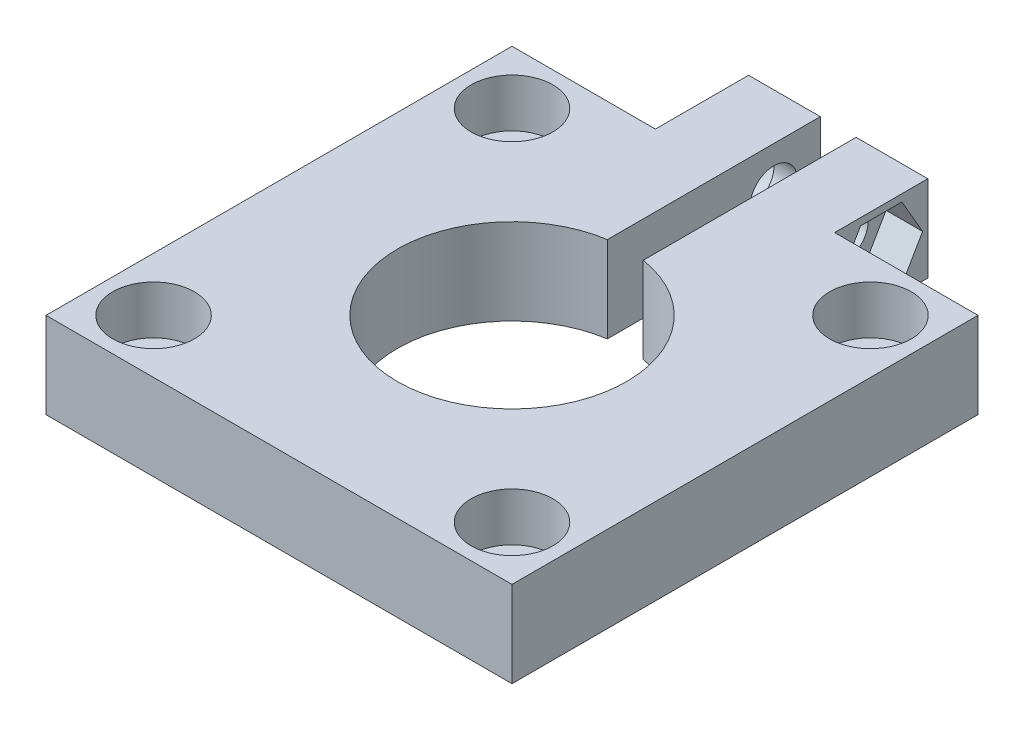
SolidWorks part; units mm, degrees
ref_plane "Front Plane" through (0, 0, 0) normal (0, 0, 1) x (1, 0, 0)
ref_plane "Top Plane" through (0, 0, 0) normal (0, 1, 0) x (1, 0, 0)
ref_plane "Right Plane" through (0, 0, 0) normal (1, 0, 0) x (0, 0, -1)
sketch "Sketch1" plane through (0, 0, 0) normal (0, 1, 0) x (1, 0, 0)
  line L1 (-32.5, 32.5) -> (32.5, 32.5)
  line L2 (-32.5, 32.5) -> (-32.5, -32.5)
  line L3 (-32.5, -32.5) -> (32.5, -32.5)
  line L4 (32.5, 32.5) -> (32.5, -32.5)
  line L5 (-32.5, 32.5) -> (32.5, -32.5) construction
  line L6 (-32.5, -32.5) -> (32.5, 32.5) construction
  point P0 (0, 0)
  dimension "D1" = 65
  dimension "D2" = 65
extrude "Boss-Extrude1" add sketch "Sketch1" along normal blind 12
sketch "Sketch3" plane through (0, 12, 0) normal (0, 1, 0) x (-1, 0, 0)
  circle A0 centre (0, 0) radius 16
  dimension "D1" = 32
extrude "Cut-Extrude1" cut sketch "Sketch3" against normal blind 12
sketch "Sketch4" plane through (0, 12, 0) normal (0, 1, 0) x (-1, 0, 0)
  line L0 (-32.5, -32.5) -> (32.5, -32.5) construction
  line L1 (2.5, -52.5) -> (-2.5, -52.5)
  line L2 (2.5, -52.5) -> (2.5, -12.5)
  line L3 (2.5, -12.5) -> (-2.5, -12.5)
  line L4 (-2.5, -52.5) -> (-2.5, -12.5)
  line L5 (2.5, -52.5) -> (-2.5, -12.5) construction
  line L6 (2.5, -12.5) -> (-2.5, -52.5) construction
  point P0 (0, -32.5)
  dimension "D1" = 40
extrude "Cut-Extrude2" cut sketch "Sketch4" against normal blind 12
sketch "Sketch5" plane through (0, 12, 0) normal (0, 1, 0) x (-1, 0, 0)
  line L1 (2.5, -32.5) -> (12.5, -32.5)
  line L2 (2.5, -32.5) -> (2.5, -45.5)
  line L3 (2.5, -45.5) -> (12.5, -45.5)
  line L4 (12.5, -32.5) -> (12.5, -45.5)
  dimension "D1" = 13
  dimension "D2" = 10
extrude "Boss-Extrude4" add sketch "Sketch5" against normal blind 12
pattern_linear "LPattern1" count 2 spacing 15 along (1, 0, 0) of "Boss-Extrude4"
hole_wizard "CBORE for M6 Hex Socket Head Cap Screw1" positions "Sketch7" profile "Sketch6" counterbore size "M6" standard "DIN" end condition through all
sketch "Sketch7" plane through (-12.5, 0, 0) normal (-1, 0, 0) x (0, 0, 1)
  line L0 (-45.5, 0) -> (-32.5, 0) construction
  line L1 (-45.5, 0) -> (-45.5, 12) construction
  point P0 (-39, 6)
  point P10 (-39, 0)
  point P11 (-45.5, 6)
  dimension "D1" = 0
  dimension "D2" = 0
sketch "Sketch6" plane through (-12.5, 6, -39) normal (0, 1, 0) x (0, 0, 1)
  line L0 (0, 0) -> (0, 45)
  line L1 (0, 45) -> (3.3, 45)
  line L3 (3.3, 45) -> (3.3, 6.75)
  line L4 (3.3, 6.75) -> (5.25, 6.75)
  line L5 (5.25, 6.75) -> (5.25, 0)
  line L7 (5.25, 0) -> (0, 0)
  line L11 (0, -6.35) -> (0, 107.95) construction
  dimension "Thru Hole Dia." = 6.6
  dimension "Thru Hole Depth" = 45
  dimension "C'Bore Dia." = 10.5
  dimension "C'Bore Depth" = 6.75
sketch "Sketch9" plane through (12.5, 0, 0) normal (1, 0, 0) x (0, 0, -1)
  line L0 (32.5, 0) -> (45.5, 0) construction
  line L1 (44.7735, 6) -> (41.8868, 11)
  line L2 (41.8868, 11) -> (36.1132, 11)
  line L3 (36.1132, 11) -> (33.2265, 6)
  line L4 (33.2265, 6) -> (36.1132, 1)
  line L5 (36.1132, 1) -> (41.8868, 1)
  line L6 (41.8868, 1) -> (44.7735, 6)
  line L8 (45.5, 0) -> (45.5, 12) construction
  circle A0 centre (39, 6) radius 5 construction
  point P1 (39, 0)
  point P11 (45.5, 6)
  dimension "D1" = 5
  dimension "D2" = 0
  dimension "D3" = 0
extrude "Cut-Extrude3" cut sketch "Sketch9" against normal blind 5.1
hole_wizard "CBORE for M6 Hex Socket Head Cap Screw2" positions "Sketch11" profile "Sketch10" counterbore size "M6" standard "DIN" end condition through all
sketch "Sketch11" plane through (0, 12, 0) normal (0, 1, 0) x (-1, 0, 0)
  point P0 (25, -25)
  dimension "D1" = 25
  dimension "D2" = 25
sketch "Sketch10" plane through (-25, 12, -25) normal (1, 0, 0) x (0, 0, 1)
  line L0 (0, 0) -> (0, 12)
  line L1 (0, 12) -> (3.75, 12)
  line L3 (3.75, 12) -> (3.75, 6.75)
  line L4 (3.75, 6.75) -> (5.7, 6.75)
  line L5 (5.7, 6.75) -> (5.7, 0)
  line L7 (5.7, 0) -> (0, 0)
  line L11 (0, -6.35) -> (0, 107.95) construction
  dimension "Thru Hole Dia." = 7.5
  dimension "Thru Hole Depth" = 12
  dimension "C'Bore Dia." = 11.4
  dimension "C'Bore Depth" = 6.75
hole_wizard "CBORE for M6 Hex Socket Head Cap Screw3" positions "Sketch13" profile "Sketch12" counterbore size "M6" standard "DIN" end condition through all
sketch "Sketch13" plane through (0, 12, 0) normal (0, 1, 0) x (-1, 0, 0)
  point P0 (-25, -25)
  dimension "D1" = 25
  dimension "D2" = 25
sketch "Sketch12" plane through (25, 12, -25) normal (1, 0, 0) x (0, 0, 1)
  line L0 (0, 0) -> (0, 12)
  line L1 (0, 12) -> (3.75, 12)
  line L3 (3.75, 12) -> (3.75, 6.75)
  line L4 (3.75, 6.75) -> (5.7, 6.75)
  line L5 (5.7, 6.75) -> (5.7, 0)
  line L7 (5.7, 0) -> (0, 0)
  line L11 (0, -6.35) -> (0, 107.95) construction
  dimension "Thru Hole Dia." = 7.5
  dimension "Thru Hole Depth" = 12
  dimension "C'Bore Dia." = 11.4
  dimension "C'Bore Depth" = 6.75
hole_wizard "CBORE for M6 Hex Socket Head Cap Screw4" positions "Sketch15" profile "Sketch14" counterbore size "M6" standard "DIN" end condition through all
sketch "Sketch15" plane through (0, 12, 0) normal (0, 1, 0) x (-1, 0, 0)
  point P0 (-25, 25)
  dimension "D1" = 25
  dimension "D2" = 25
sketch "Sketch14" plane through (25, 12, 25) normal (1, 0, 0) x (0, 0, 1)
  line L0 (0, 0) -> (0, 12)
  line L1 (0, 12) -> (3.75, 12)
  line L3 (3.75, 12) -> (3.75, 6.75)
  line L4 (3.75, 6.75) -> (5.7, 6.75)
  line L5 (5.7, 6.75) -> (5.7, 0)
  line L7 (5.7, 0) -> (0, 0)
  line L11 (0, -6.35) -> (0, 107.95) construction
  dimension "Thru Hole Dia." = 7.5
  dimension "Thru Hole Depth" = 12
  dimension "C'Bore Dia." = 11.4
  dimension "C'Bore Depth" = 6.75
hole_wizard "CBORE for M6 Hex Socket Head Cap Screw5" positions "Sketch17" profile "Sketch16" counterbore size "M6" standard "DIN" end condition through all
sketch "Sketch17" plane through (0, 12, 0) normal (0, 1, 0) x (-1, 0, 0)
  point P0 (25, 25)
  dimension "D1" = 25
  dimension "D2" = 25
sketch "Sketch16" plane through (-25, 12, 25) normal (1, 0, 0) x (0, 0, 1)
  line L0 (0, 0) -> (0, 12)
  line L1 (0, 12) -> (3.75, 12)
  line L3 (3.75, 12) -> (3.75, 6.75)
  line L4 (3.75, 6.75) -> (5.7, 6.75)
  line L5 (5.7, 6.75) -> (5.7, 0)
  line L7 (5.7, 0) -> (0, 0)
  line L11 (0, -6.35) -> (0, 107.95) construction
  dimension "Thru Hole Dia." = 7.5
  dimension "Thru Hole Depth" = 12
  dimension "C'Bore Dia." = 11.4
  dimension "C'Bore Depth" = 6.75
